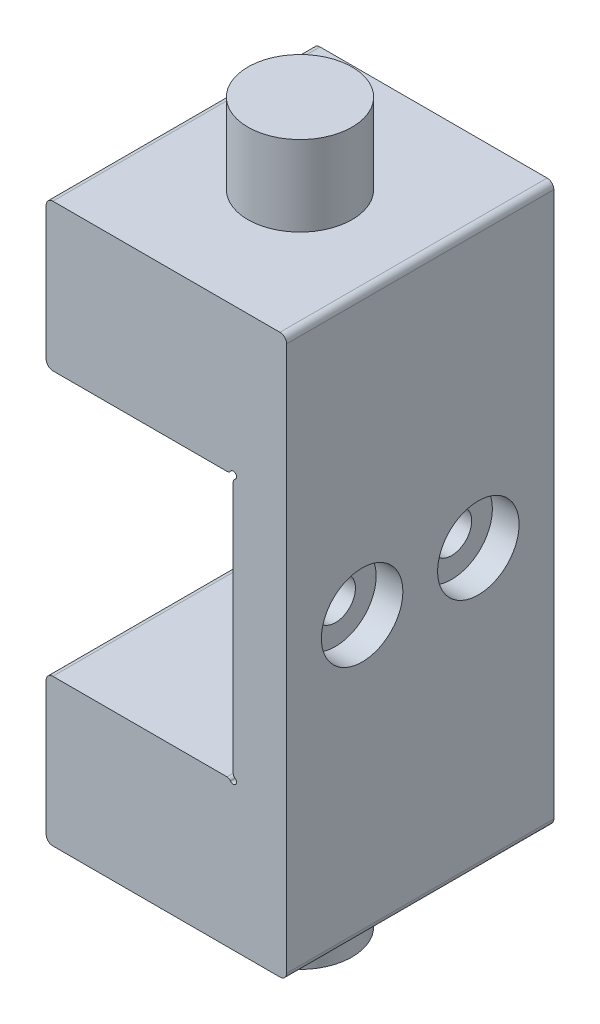
SolidWorks part; units mm, degrees
ref_plane "Front Plane" through (0, 0, 0) normal (0, 0, 1) x (1, 0, 0)
ref_plane "Top Plane" through (0, 0, 0) normal (0, 1, 0) x (1, 0, 0)
ref_plane "Right Plane" through (0, 0, 0) normal (1, 0, 0) x (0, 0, -1)
sketch "Sketch1" plane through (0, 0, 0) normal (0, 0, 1) x (1, 0, 0)
  line L0 (0, 0) -> (-14, 0)
  line L1 (-14, 0) -> (-14, -11)
  line L2 (-14, -11) -> (4, -11)
  line L3 (4, -11) -> (4, 30.8)
  line L5 (0, 19.8) -> (0, 0)
  line L6 (-14, 30.8) -> (4, 30.8)
  line L7 (-14, 30.8) -> (-14, 19.8)
  line L8 (-14, 19.8) -> (0, 19.8)
  dimension "D1" = 19.8
  dimension "D2" = 14
  dimension "D3" = 11
  dimension "D4" = 4
extrude "Boss-Extrude1" add sketch "Sketch1" along normal blind 20
sketch "Sketch3" plane through (4, 0, 0) normal (1, 0, 0) x (0, 0, -1)
  line L0 (-20, 9.9) -> (-17.4, 9.9) construction
  line L1 (0, 19.8) -> (0, 0) construction
  line L2 (0, 19.8) -> (0, 0) construction
  line L6 (-20, -11) -> (-20, 30.8) construction
  line L7 (-17.4, 9.9) -> (-11.3, 9.9) construction
  line L8 (-11.3, 9.9) -> (-8.7, 9.9) construction
  line L9 (-8.7, 9.9) -> (-2.6, 9.9) construction
  line L10 (-2.6, 9.9) -> (0, 9.9) construction
  circle A0 centre (-5.65, 9.9) radius 1.5
  circle A1 centre (-14.35, 9.9) radius 1.5
  circle A2 centre (-14.35, 9.9) radius 3.05 construction
  circle A3 centre (-5.65, 9.9) radius 3.05 construction
  point P7 (0, 9.9)
  dimension "D1" = 3
  dimension "D2" = 6.1
sketch "Sketch5" plane through (0, 0, 20) normal (0, 0, 1) x (1, 0, 0)
  circle A0 centre (0, 0) radius 0.25
  circle A1 centre (0, 19.8) radius 0.25
  dimension "D1" = 0.5
extrude "Cut-Extrude3" cut sketch "Sketch5" against normal up to next
extrude "Cut-Extrude4" cut sketch "Sketch3" against normal up to next
fillet "Fillet3" radius 0.3 4 edges at (-0.25, 0, 10) (0, 0.25, 10) (-0.25, 19.8, 10) (0, 19.55, 10)
sketch "Sketch12" plane through (0, -11, 0) normal (0, -1, 0) x (1, 0, 0)
  line L0 (4, 20) -> (4, 0) construction
  line L1 (-14, 0) -> (4, 0) construction
  circle A0 centre (-5, 10) radius 3.9
  point P4 (4, 10)
  point P7 (-5, 0)
  dimension "D1" = 7.8
extrude "Boss-Extrude3" add sketch "Sketch12" along normal blind 6
sketch "Sketch13" plane through (0, 30.8, 0) normal (0, 1, 0) x (1, 0, 0)
  line L0 (4, -20) -> (4, 0) construction
  line L1 (4, 0) -> (-14, 0) construction
  circle A0 centre (-5, -10) radius 3.9
  point P4 (4, -10)
  point P7 (-5, 0)
  dimension "D1" = 7.8
extrude "Boss-Extrude4" add sketch "Sketch13" along normal blind 6 contours A0
fillet "Fillet4" radius 0.5 6 edges at (-14, 30.8, 10) (-14, 0, 10) (-14, 19.8, 10) (4, 30.8, 10) (4, -11, 10) (-14, -11, 10)
sketch "Sketch14" plane through (4, 0, 0) normal (1, 0, 0) x (0, 0, -1)
  circle A0 centre (-14.35, 9.9) radius 3.05
  circle A1 centre (-5.65, 9.9) radius 3.05
  dimension "D1" = 6.1
extrude "Cut-Extrude5" cut sketch "Sketch14" against normal blind 2
sketch "Sketch15" plane through (0, 0, 0) normal (0, 0, -1) x (-1, 0, 0)
  line L1 (21.5981, 41.0618) -> (-9.1402, 41.0618)
  line L2 (21.5981, 41.0618) -> (21.5981, 19.339)
  line L3 (21.5981, 19.339) -> (-9.1402, 19.339)
  line L4 (-9.1402, 41.0618) -> (-9.1402, 19.339)
extrude "Cut-Extrude6" [suppressed] cut sketch "Sketch15" against normal up to surface (20 mm away)
